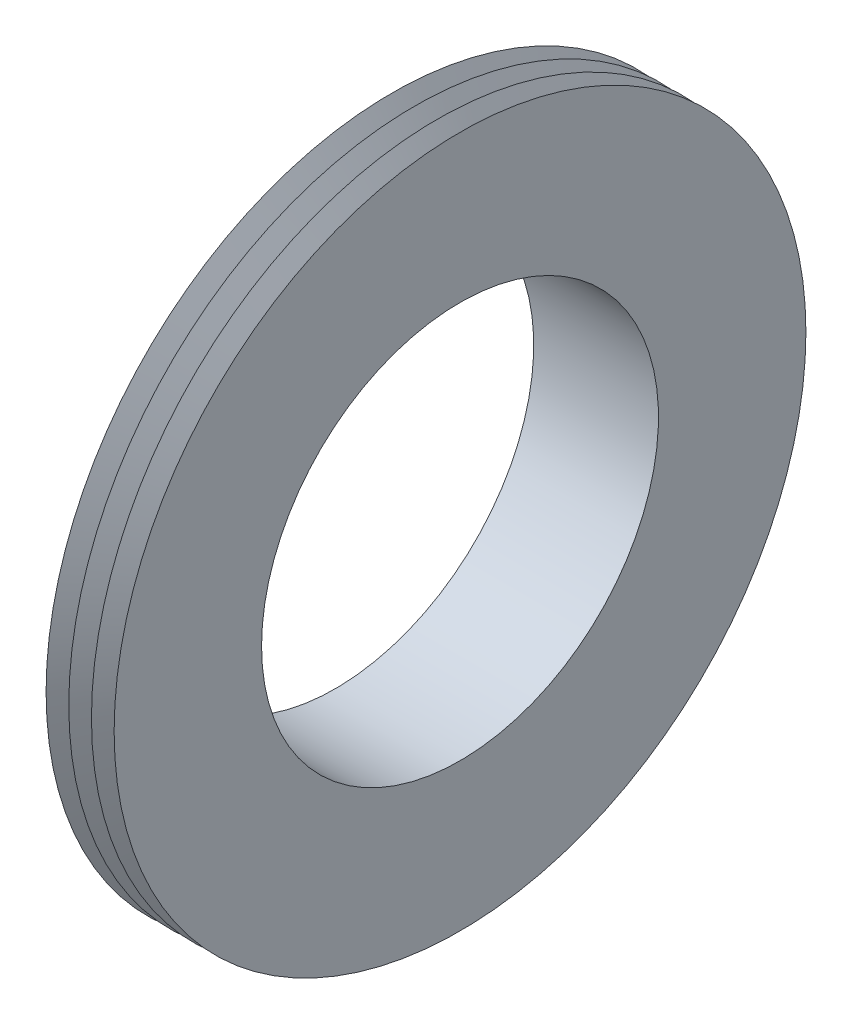
SolidWorks part; units mm, degrees
ref_plane "前视基准面" through (0, 0, 0) normal (0, 0, 1) x (1, 0, 0)
ref_plane "上视基准面" through (0, 0, 0) normal (0, 1, 0) x (1, 0, 0)
ref_plane "右视基准面" through (0, 0, 0) normal (1, 0, 0) x (0, 0, -1)
sketch "草图1" plane through (0, 0, 0) normal (0, 0, 1) x (1, 0, 0)
  line L0 (0, 0) -> (0, 17.5)
  line L1 (0, 17.5) -> (11, 17.5)
  line L2 (0, 17.5) -> (0, 21.5)
  line L3 (0, 21.5) -> (5, 21.5)
  line L4 (5, 21.5) -> (5, 30.5)
  line L5 (0, 0) -> (11, 0)
  line L6 (5, 30.5) -> (6, 28.7679)
  line L7 (6, 28.7679) -> (7, 30.5)
  line L8 (7, 30.5) -> (8, 28.7679)
  line L9 (8, 28.7679) -> (9, 30.5)
  line L10 (9, 30.5) -> (10, 28.7679)
  line L11 (10, 28.7679) -> (11, 30.5)
  line L14 (11, 30.5) -> (11, 17.5)
revolve "旋转1" add sketch "草图1" angle 360 about L5
